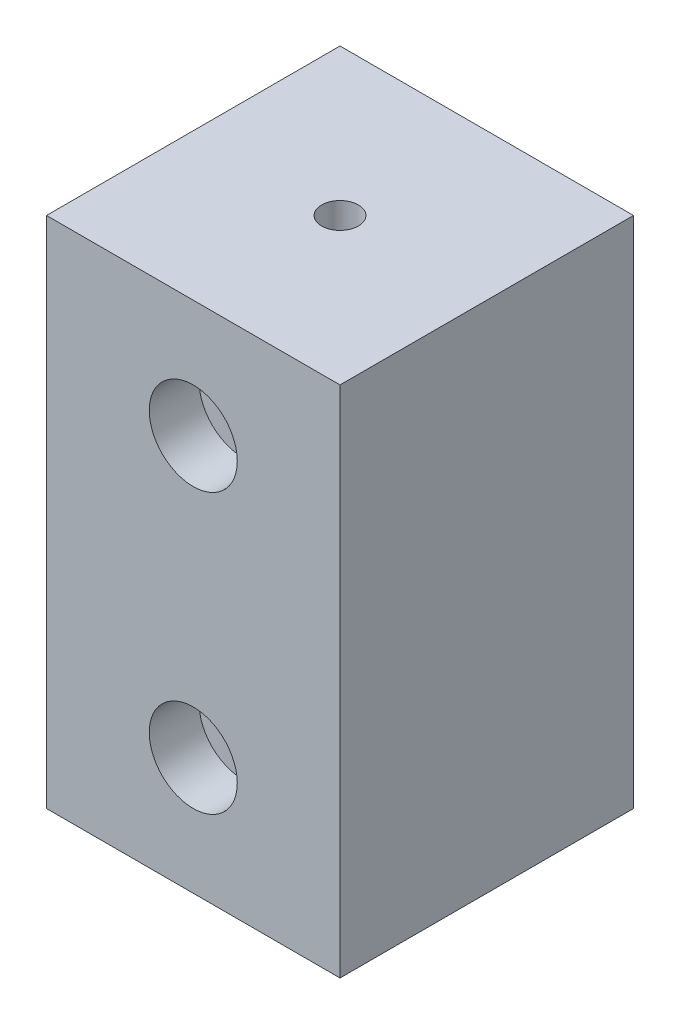
SolidWorks part; units mm, degrees
material "AISI Type 316L stainless steel"
ref_plane "Front Plane" through (0, 0, 0) normal (0, 0, 1) x (1, 0, 0)
ref_plane "Top Plane" through (0, 0, 0) normal (0, 1, 0) x (1, 0, 0)
ref_plane "Right Plane" through (0, 0, 0) normal (1, 0, 0) x (0, 0, -1)
sketch "Sketch1" plane through (0, 0, 0) normal (0, 0, 1) x (1, 0, 0)
  line L0 (-10, 17.5) -> (10, -17.5) construction
  line L1 (-10, 17.5) -> (10, 17.5)
  line L2 (-10, 17.5) -> (-10, -17.5)
  line L3 (-10, -17.5) -> (10, -17.5)
  line L4 (10, 17.5) -> (10, -17.5)
  dimension "D1" = 35
  dimension "D2" = 20
extrude "Boss-Extrude1" add sketch "Sketch1" along normal blind 20 contours L2 L3 L4 L1
sketch "Sketch2" plane through (0, 0, 20) normal (0, 0, 1) x (1, 0, 0)
  line L1 (-10, 17.5) -> (10, 17.5) construction
  line L2 (-10, -17.5) -> (10, -17.5) construction
  point P0 (0, 9.5)
  point P1 (0, -9.5)
  dimension "D1" = 8
  dimension "D2" = 8
hole_wizard "CBORE for M3 Hexagon socket head cap screws1" positions "3DSketch1" profile "Sketch3" counterbore size "M3" standard "GB"
sketch3d "3DSketch1"
  point P0 (0, 9.5, 20)
  point P3 (0, -9.5, 20)
sketch "Sketch3" plane through (0, 9.5, 20) normal (1, 0, 0) x (0, -1, 0)
  line L0 (0, 0) -> (0, 20)
  line L1 (0, 20) -> (1.6, 20)
  line L3 (1.6, 20) -> (1.6, 3.4)
  line L4 (1.6, 3.4) -> (3, 3.4)
  line L5 (3, 3.4) -> (3, 0)
  line L7 (3, 0) -> (0, 0)
  line L11 (0, -6.35) -> (0, 107.95) construction
  dimension "Thru Hole Dia." = 3.2
  dimension "Thru Hole Depth" = 20
  dimension "C'Bore Dia." = 6
  dimension "C'Bore Depth" = 3.4
hole_wizard "Tap Drill for M3 Tap1" positions "Sketch4" profile "Sketch6" hole size "M3" standard "GB"
sketch "Sketch4" plane through (0, 17.5, 0) normal (0, 1, 0) x (1, 0, 0)
  line L0 (-10, 0) -> (10, -20) construction
  point P0 (0, -10)
sketch "Sketch6" plane through (0, 17.5, 10) normal (1, 0, 0) x (0, 0, 1)
  line L0 (0, 0) -> (0, 5.7511)
  line L1 (0, 5.7511) -> (1.25, 5)
  line L2 (1.25, 5) -> (1.25, 0)
  line L5 (1.25, 0) -> (0, 0)
  line L10 (0, 5.7511) -> (-1.25, 5) construction
  line L11 (0, -6.35) -> (0, 107.95) construction
  dimension "Hole Dia." = 2.5
  dimension "Hole Depth" = 5
  dimension "Drill Angle" = 118
